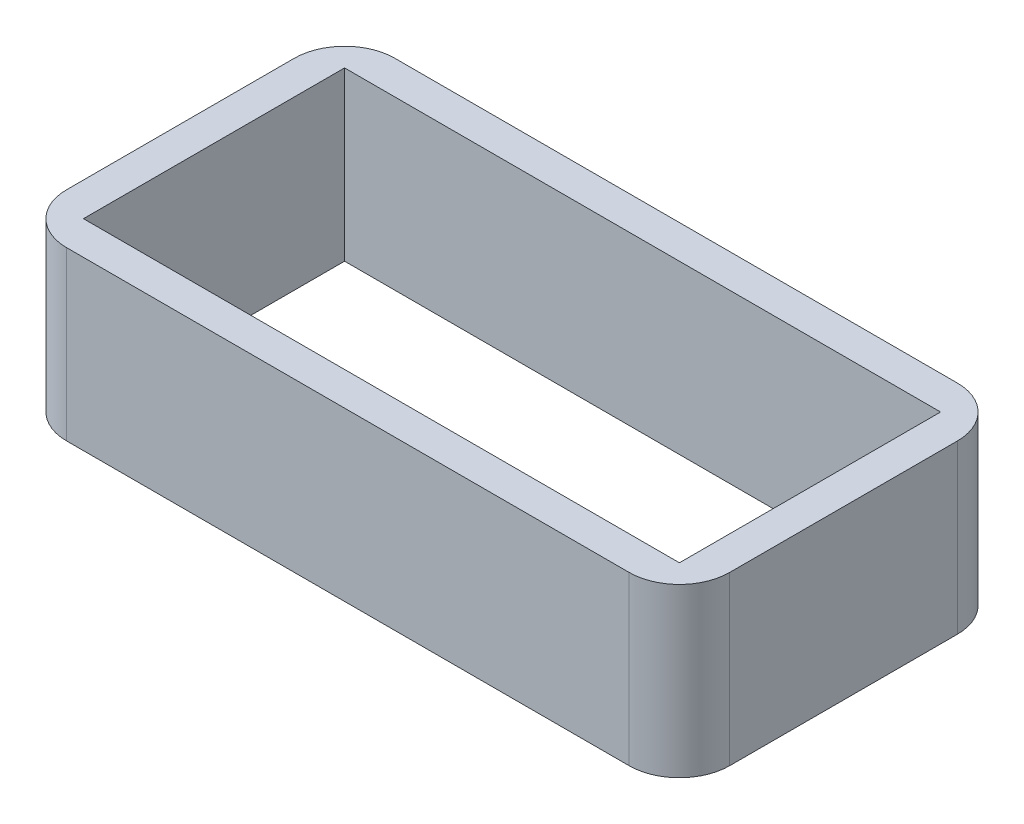
SolidWorks part; units mm, degrees
ref_plane "Front Plane" through (0, 0, 0) normal (0, 0, 1) x (1, 0, 0)
ref_plane "Top Plane" through (0, 0, 0) normal (0, 1, 0) x (1, 0, 0)
ref_plane "Right Plane" through (0, 0, 0) normal (1, 0, 0) x (0, 0, -1)
sketch "Sketch2" plane through (0, 0, 0) normal (0, 1, 0) x (1, 0, 0)
  line L0 (-17.8, 7.8) -> (-17.8, -7.8)
  line L1 (-17.5, 7.5) -> (17.5, 7.5)
  line L2 (-17.5, 7.5) -> (-17.5, -7.5)
  line L3 (-17.5, -7.5) -> (17.5, -7.5)
  line L4 (17.5, 7.5) -> (17.5, -7.5)
  line L5 (-17.5, 7.5) -> (17.5, -7.5) construction
  line L6 (-17.5, -7.5) -> (17.5, 7.5) construction
  line L7 (-17.8, -7.8) -> (17.8, -7.8)
  line L8 (17.8, 7.8) -> (17.8, -7.8)
  line L9 (-17.8, 7.8) -> (17.8, 7.8)
  line L10 (-19.8, 9.8) -> (-19.8, -9.8)
  line L11 (-19.8, -9.8) -> (19.8, -9.8)
  line L12 (19.8, 9.8) -> (19.8, -9.8)
  line L13 (-19.8, 9.8) -> (19.8, 9.8)
  point P0 (0, 0)
  dimension "D1" = 35
  dimension "D2" = 15
  dimension "D3" = 0.3
  dimension "D4" = 2
extrude "Boss-Extrude2" add sketch "Sketch2" along normal blind 10 contours L13 L10 L11 L12 L0 L9 L8 L7
fillet "Fillet2" radius 3 4 edges at (-19.8, 5, -9.8) (19.8, 5, -9.8) (19.8, 5, 9.8) (-19.8, 5, 9.8)
